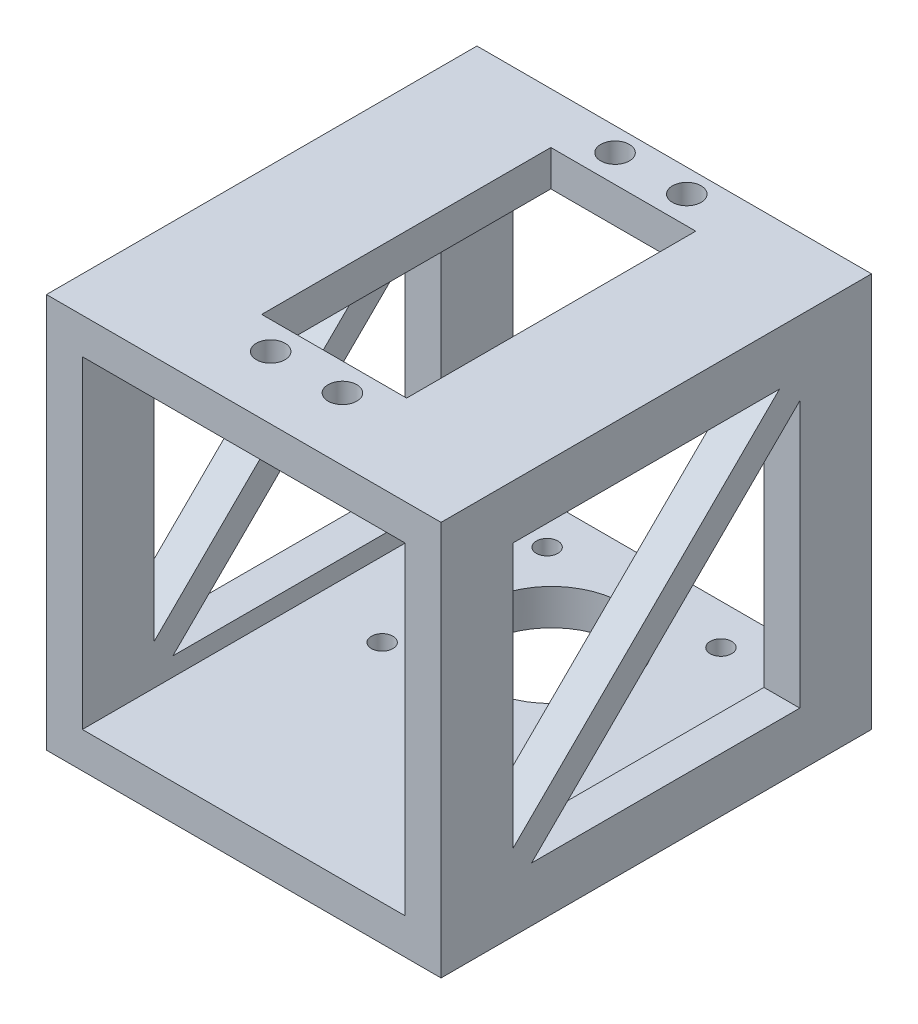
SolidWorks part; units mm, degrees
material "Alliage 1060"
ref_plane "Plan de face" through (0, 0, 0) normal (0, 0, 1) x (1, 0, 0)
ref_plane "Plan de dessus" through (0, 0, 0) normal (0, 1, 0) x (1, 0, 0)
ref_plane "Plan de droite" through (0, 0, 0) normal (1, 0, 0) x (0, 0, -1)
sketch "Esquisse1" plane through (0, 0, 0) normal (0, 0, 1) x (1, 0, 0)
  line L0 (-41.5827, 29.5248) -> (3.4173, 29.5248)
  line L1 (-46.5827, 34.5248) -> (8.4173, 34.5248)
  line L2 (-46.5827, 34.5248) -> (-46.5827, -20.4752)
  line L3 (-46.5827, -20.4752) -> (8.4173, -20.4752)
  line L4 (8.4173, 34.5248) -> (8.4173, -20.4752)
  line L5 (3.4173, 29.5248) -> (3.4173, -15.4752)
  line L6 (-41.5827, -15.4752) -> (3.4173, -15.4752)
  line L7 (-41.5827, 29.5248) -> (-41.5827, -15.4752)
  dimension "D1" = 55
  dimension "D2" = 55
  dimension "D3" = 5
extrude "Boss.-Extru.1" add sketch "Esquisse1" along normal blind 60
sketch "Esquisse2" plane through (0, 34.5248, 0) normal (0, 1, 0) x (1, 0, 0)
  line L0 (-30.25, 0) -> (30.25, 0) construction
  line L1 (-29.1827, -7.1) -> (-8.9827, -7.1)
  line L2 (-29.1827, -7.1) -> (-29.1827, -47.4)
  line L3 (-29.1827, -47.4) -> (-8.9827, -47.4)
  line L4 (-8.9827, -7.1) -> (-8.9827, -47.4)
  line L5 (-46.5827, -60) -> (-46.5827, 0) construction
  line L7 (8.4173, -60) -> (8.4173, 0) construction
  circle A0 centre (-24.0827, -3.25) radius 2
  circle A1 centre (-14.0827, -3.25) radius 2
  circle A2 centre (-24.0827, -51.25) radius 2
  circle A3 centre (-14.0827, -51.25) radius 2
  point P18 (0, 0)
  dimension "D5" = 4
  dimension "D6" = 4
  dimension "D11" = 4
  dimension "4" = 4
  dimension "D1" = 20.2
  dimension "D2" = 40.3
  dimension "D3" = 7.1
  dimension "D4" = 17.4
  dimension "D7" = 3.25
  dimension "D8" = 3.25
  dimension "D9" = 22.5
  dimension "D10" = 22.5
  dimension "D12" = 3.85
  dimension "D13" = 3.85
extrude "Enlèv. mat.-Extru.1" cut sketch "Esquisse2" against normal blind 10
sketch "Esquisse5" plane through (0, -20.4752, 0) normal (0, -1, 0) x (1, 0, 0)
  line L0 (8.4173, 60) -> (8.4173, 0) construction
  line L1 (30.25, 0) -> (-30.25, 0) construction
  line L7 (-6.9684, 5.6051) -> (-31.197, 28.5949) construction
  line L8 (-6.9684, 28.5949) -> (-31.197, 5.6051) construction
  circle A0 centre (-19.0827, 17.1) radius 10
  circle A1 centre (-31.197, 5.6051) radius 1.5
  circle A2 centre (-6.9684, 5.6051) radius 1.5
  circle A3 centre (-31.197, 28.5949) radius 1.5
  circle A4 centre (-6.9684, 28.5949) radius 1.5
  dimension "D2" = 20
  dimension "D5" = 3
  dimension "D6" = 3
  dimension "D7" = 3
  dimension "D8" = 3
  dimension "D1" = 27.5
  dimension "D3" = 17.1
  dimension "D4" = 33.4
extrude "Enlèv. mat.-Extru.2" cut sketch "Esquisse5" against normal blind 10
sketch "Esquisse8" plane through (8.4173, 0, 0) normal (1, 0, 0) x (0, 0, -1)
  line L0 (-60, -20.4752) -> (-60, 34.5248) construction
  line L1 (-60, 34.5248) -> (0, 34.5248) construction
  line L2 (-50, 27.0248) -> (-12.8284, 27.0248)
  line L3 (-50, 27.0248) -> (-50, -9.8599)
  line L4 (-47.3839, -12.899) -> (-10, -12.899)
  line L5 (-10, 24.1964) -> (-10, -12.899)
  line L6 (-60, -20.4752) -> (0, -20.4752) construction
  line L8 (-50, -9.8599) -> (-12.8284, 27.0248)
  line L9 (-47.3839, -12.899) -> (-10, 24.1964)
  point P3 (0, 0)
  point P4 (0, 0)
  point P14 (0, 0)
  point P16 (-10, 24.1963)
  dimension "D2" = 40
  dimension "D3" = 10
  dimension "D4" = 7.5
  dimension "D5" = 7.5762
extrude "Enlèv. mat.-Extru.3" cut sketch "Esquisse8" against normal through all
